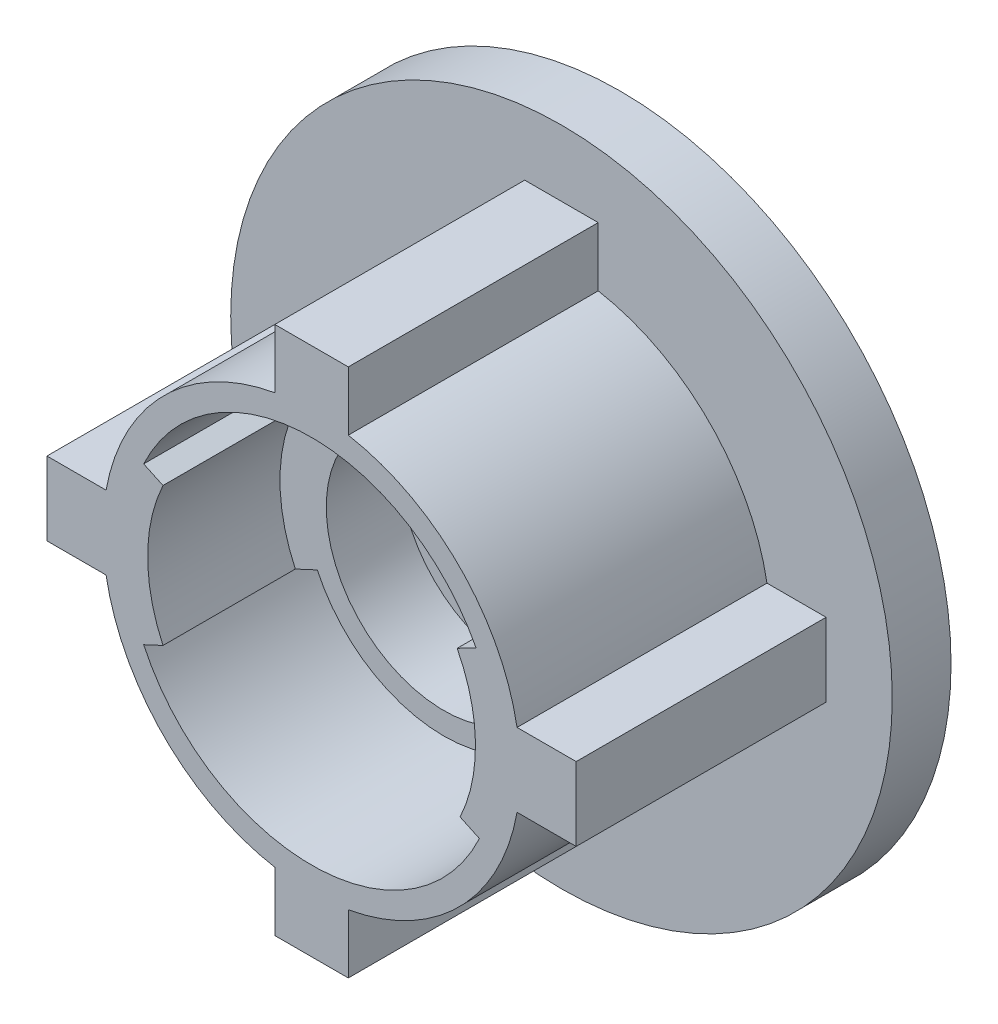
SolidWorks part; units mm, degrees
ref_plane "Plano frontal" through (0, 0, 0) normal (0, 0, 1) x (1, 0, 0)
ref_plane "Plano superior" through (0, 0, 0) normal (0, 1, 0) x (1, 0, 0)
ref_plane "Plano direito" through (0, 0, 0) normal (1, 0, 0) x (0, 0, -1)
sketch "Esboço1" plane through (0, 0, 0) normal (0, 0, 1) x (1, 0, 0)
  line L0 (18, 2.5) -> (13.9782, 2.5)
  line L1 (18, -2.5) -> (18, 2.5)
  line L2 (13.9782, -2.5) -> (18, -2.5)
  line L3 (2.5, -18) -> (2.5, -13.9782)
  line L4 (-2.5, -18) -> (2.5, -18)
  line L5 (-2.5, -13.9782) -> (-2.5, -18)
  line L6 (-18, -2.5) -> (-13.9782, -2.5)
  line L7 (-18, 2.5) -> (-18, -2.5)
  line L8 (-13.9782, 2.5) -> (-18, 2.5)
  line L9 (-2.5, 18) -> (-2.5, 13.9782)
  line L10 (2.5, 18) -> (-2.5, 18)
  line L11 (2.5, 13.9782) -> (2.5, 18)
  circle A0 centre (0, 0) radius 11.15
  circle A1 centre (0, 0) radius 6.1
  circle A3 centre (0, 0) radius 4.3
  arc A4 (-13.9782, -2.5) -> (-2.5, -13.9782) centre (0, 0) ccw
  arc A5 (13.9782, 2.5) -> (2.5, 13.9782) centre (0, 0) ccw
  arc A6 (2.5, -13.9782) -> (13.9782, -2.5) centre (0, 0) ccw
  arc A7 (-13.9782, -2.5) -> (-2.5, -13.9782) centre (0, 0) ccw
  arc A8 (-2.5, 13.9782) -> (-13.9782, 2.5) centre (0, 0) ccw
  arc A9 (-2.5, 13.9782) -> (-13.9782, 2.5) centre (0, 0) ccw
  arc A10 (13.9782, 2.5) -> (2.5, 13.9782) centre (0, 0) ccw
  arc A11 (2.5, -13.9782) -> (13.9782, -2.5) centre (0, 0) ccw
  dimension "D1" = 28.4
  dimension "D2" = 8.6
  dimension "D3" = 12.2
  dimension "D5" = 22.3
  dimension "D6" = 14.2
  dimension "D7" = 14.2
  dimension "D8" = 14.2
  dimension "D9" = 14.2
  dimension "D10" = 2.5
  dimension "D11" = 2.5
  dimension "D12" = 13.9782
  dimension "D13" = 13.9782
  dimension "D14" = 18
  dimension "D15" = 18
  dimension "D16" = 2.5
  dimension "D17" = 2.5
  dimension "D18" = 13.9782
  dimension "D19" = 13.9782
  dimension "D20" = 18
  dimension "D21" = 18
  dimension "D22" = 2.5
  dimension "D23" = 2.5
  dimension "D24" = 13.9782
  dimension "D25" = 13.9782
  dimension "D26" = 18
  dimension "D27" = 18
  dimension "D28" = 2.5
  dimension "D29" = 2.5
  dimension "D30" = 13.9782
  dimension "D31" = 13.9782
  dimension "D32" = 18
  dimension "D33" = 18
extrude "Ressalto-extrusão1" add sketch "Esboço1" along normal blind 15 contours L9 A8 L8 L7 L6 A4 L5 L4 L3 A6 L2 L1 L0 A5 L11 L10 A0
sketch "Esboço2" plane through (0, 0, 0) normal (0, 0, -1) x (-1, 0, 0)
  line L4 (2.5, 18) -> (2.5, 13.9782) construction
  line L5 (-2.5, 18) -> (2.5, 18) construction
  circle A0 centre (0, 0) radius 22.5
  arc A9 (2.5, 13.9782) -> (-13.9782, -2.5) centre (0, 0) ccw
  arc A10 (-13.9782, -2.5) -> (2.5, -13.9782) centre (0, 0) ccw
  arc A11 (-2.5, -13.9782) -> (13.9782, -2.5) centre (0, 0) ccw
  arc A12 (13.9782, -2.5) -> (2.5, 13.9782) centre (0, 0) ccw
  line M18 (2.5, 13.9782) -> (2.5, 18)
  line M19 (2.5, 18) -> (-2.5, 18)
  line M20 (-2.5, 18) -> (-2.5, 13.9782)
  arc M21 (-2.5, 13.9782) -> (-13.9782, 2.5) centre (0, 0) ccw
  line M22 (-13.9782, 2.5) -> (-18, 2.5)
  line M23 (-18, 2.5) -> (-18, -2.5)
  line M24 (-18, -2.5) -> (-13.9782, -2.5)
  arc M25 (-13.9782, -2.5) -> (-2.5, -13.9782) centre (0, 0) ccw
  line M26 (-2.5, -13.9782) -> (-2.5, -18)
  line M27 (-2.5, -18) -> (2.5, -18)
  line M28 (2.5, -18) -> (2.5, -13.9782)
  arc M29 (2.5, -13.9782) -> (13.9782, -2.5) centre (0, 0) ccw
  line M30 (13.9782, -2.5) -> (18, -2.5)
  line M31 (18, -2.5) -> (18, 2.5)
  line M32 (18, 2.5) -> (13.9782, 2.5)
  arc M33 (13.9782, 2.5) -> (2.5, 13.9782) centre (0, 0) ccw
  dimension "D1" = 45
  dimension "D2" = 14.2
  dimension "D3" = 14.2
  dimension "D4" = 14.2
  dimension "D5" = 14.2
  dimension "D6" = 11.4782
  dimension "D7" = 2.5
  dimension "D8" = 5
  dimension "D9" = 16.4782
  dimension "D10" = 4.0218
  dimension "D11" = 18
  dimension "D12" = 31.9782
  dimension "D14" = 20.5
  dimension "D15" = 20.5
  dimension "D16" = 31.9782
extrude "Ressalto-extrusão2" add sketch "Esboço2" along normal blind 4 separate body contours A0 M18 M33 M32 M31 M30 M29 M28 M27 M26 M25 M24 M23 M22 M21 M20 M19 | A10 M26 M27 M28 | A9 M22 M23 M24 | A9 M18 M19 M20 | A12 M30 M31 M32
sketch "Esboço5" plane through (0, 0, 15) normal (0, 0, 1) x (1, 0, 0)
  circle A0 centre (0, 0) radius 11.15 construction
  circle A1 centre (0, 0) radius 11.15
  circle A2 centre (0, 0) radius 8
  dimension "D1" = 16
extrude "Ressalto-extrusão6" add sketch "Esboço5" against normal blind 8
sketch "Esboço7" plane through (0, 0, 0) normal (0, 0, -1) x (-1, 0, 0)
  circle A0 centre (0, 0) radius 11.15 construction
  circle A1 centre (0, 0) radius 14.2 construction
  circle A2 centre (0, 0) radius 11.15
  circle A3 centre (0, 0) radius 14.2
extrude "Ressalto-extrusão7" add sketch "Esboço7" along normal up to surface (4 mm away) up to face at (-14.2, 0, -4)
sketch "Esboço8" plane through (0, 0, 7) normal (0, 0, -1) x (-1, 0, 0)
  circle A0 centre (0, 0) radius 8 construction
  circle A1 centre (0, 0) radius 11.15 construction
  circle A2 centre (0, 0) radius 8
  circle A3 centre (0, 0) radius 11.15
extrude "Ressalto-extrusão8" add sketch "Esboço8" along normal blind 4
sketch "Esboço11" plane through (0, 0, 15) normal (0, 0, 1) x (1, 0, 0)
  line L0 (-11.1912, -5.7895) -> (-8.4378, -4.3651)
  line L1 (-11.4195, 5.325) -> (-8.6099, 4.0149)
  line L2 (8.6099, -4.0149) -> (11.4195, -5.325)
  line L3 (8.4378, 4.3651) -> (11.1912, 5.7895)
  arc A2 (-8.4378, -4.3651) -> (8.6099, -4.0149) centre (0, 0) ccw
  arc A3 (-11.1912, -5.7895) -> (11.4195, -5.325) centre (0, 0) ccw
  arc A4 (8.4378, 4.3651) -> (-8.6099, 4.0149) centre (0, 0) ccw
  arc A5 (11.1912, 5.7895) -> (-11.4195, 5.325) centre (0, 0) ccw
  dimension "D1" = 19
  dimension "D2" = 25.2
extrude "Corte-extrusão1" cut sketch "Esboço11" against normal blind 7
sketch "Esboço12" plane through (0, 0, 8) normal (0, 0, 1) x (1, 0, 0)
  line L0 (11.4195, -5.325) -> (8.6099, -4.0149) construction
  line L1 (-8.4378, -4.3651) -> (-11.1912, -5.7895) construction
  line L2 (-11.4195, 5.325) -> (-8.6099, 4.0149) construction
  line L3 (8.4378, 4.3651) -> (11.1912, 5.7895) construction
  line L4 (11.4195, -5.325) -> (8.6099, -4.0149)
  line L5 (-8.4378, -4.3651) -> (-11.1912, -5.7895)
  line L6 (-11.4195, 5.325) -> (-8.6099, 4.0149)
  line L7 (8.4378, 4.3651) -> (11.1912, 5.7895)
  arc A0 (-11.1912, -5.7895) -> (11.4195, -5.325) centre (0, 0) ccw construction
  arc A1 (-8.4378, -4.3651) -> (8.6099, -4.0149) centre (0, 0) ccw construction
  arc A2 (11.1912, 5.7895) -> (-11.4195, 5.325) centre (0, 0) ccw construction
  arc A3 (8.4378, 4.3651) -> (-8.6099, 4.0149) centre (0, 0) ccw construction
  arc A4 (-11.1912, -5.7895) -> (11.4195, -5.325) centre (0, 0) ccw
  arc A5 (-8.4378, -4.3651) -> (8.6099, -4.0149) centre (0, 0) ccw
  arc A6 (11.1912, 5.7895) -> (-11.4195, 5.325) centre (0, 0) ccw
  arc A7 (8.4378, 4.3651) -> (-8.6099, 4.0149) centre (0, 0) ccw
extrude "Corte-extrusão2" cut sketch "Esboço12" against normal up to surface (8 mm away) up to face at (-22.5, 0, 0)
sketch "Esboço13" plane through (0, 0, 15) normal (0, 0, 1) x (1, 0, 0)
  line L12 (-2.5, 18) -> (-2.5, 13.9782)
  line L13 (-13.9782, 2.5) -> (-18, 2.5)
  line L14 (-18, 2.5) -> (-18, -2.5)
  line L15 (-18, -2.5) -> (-13.9782, -2.5)
  line L16 (-2.5, -13.9782) -> (-2.5, -18)
  line L17 (-2.5, -18) -> (2.5, -18)
  line L18 (2.5, -18) -> (2.5, -13.9782)
  line L19 (13.9782, -2.5) -> (18, -2.5)
  line L20 (18, -2.5) -> (18, 2.5)
  line L21 (18, 2.5) -> (13.9782, 2.5)
  line L22 (2.5, 13.9782) -> (2.5, 18)
  line L23 (2.5, 18) -> (-2.5, 18)
  line L24 (-2.5, 18) -> (-2.5, 13.9782)
  line L25 (-13.9782, 2.5) -> (-18, 2.5)
  line L26 (-18, 2.5) -> (-18, -2.5)
  line L27 (-18, -2.5) -> (-13.9782, -2.5)
  line L28 (-2.5, -13.9782) -> (-2.5, -18)
  line L29 (-2.5, -18) -> (2.5, -18)
  line L30 (2.5, -18) -> (2.5, -13.9782)
  line L31 (13.9782, -2.5) -> (18, -2.5)
  line L32 (18, -2.5) -> (18, 2.5)
  line L33 (18, 2.5) -> (13.9782, 2.5)
  line L34 (2.5, 13.9782) -> (2.5, 18)
  line L35 (2.5, 18) -> (-2.5, 18)
  arc A4 (-2.5, 13.9782) -> (-13.9782, 2.5) centre (0, 0) ccw
  arc A5 (-13.9782, -2.5) -> (-2.5, -13.9782) centre (0, 0) ccw
  arc A6 (2.5, -13.9782) -> (13.9782, -2.5) centre (0, 0) ccw
  arc A7 (13.9782, 2.5) -> (2.5, 13.9782) centre (0, 0) ccw
  arc A8 (-2.5, 13.9782) -> (-13.9782, 2.5) centre (0, 0) ccw
  arc A9 (-13.9782, -2.5) -> (-2.5, -13.9782) centre (0, 0) ccw
  arc A10 (2.5, -13.9782) -> (13.9782, -2.5) centre (0, 0) ccw
  arc A11 (13.9782, 2.5) -> (2.5, 13.9782) centre (0, 0) ccw
  dimension "D1" = 0
extrude "Corte-extrusão3" cut sketch "Esboço13" against normal blind 4
sketch "Esboço14" plane through (0, 0, 11) normal (0, 0, 1) x (1, 0, 0)
  line L0 (11.1912, 5.7895) -> (8.4378, 4.3651) construction
  line L1 (-8.6099, 4.0149) -> (-11.4195, 5.325) construction
  line L2 (11.1912, 5.7895) -> (8.4378, 4.3651)
  line L3 (-8.6099, 4.0149) -> (-11.4195, 5.325)
  line L4 (0, 0) -> (5.7325, 0) construction
  line L5 (-8.6099, -4.0149) -> (-11.4195, -5.325)
  line L7 (-11.1912, -5.7895) -> (-8.4378, -4.3651) construction
  line L8 (-11.1912, -5.7895) -> (-8.4378, -4.3651)
  arc A0 (8.4378, 4.3651) -> (-8.6099, 4.0149) centre (0, 0) ccw construction
  arc A1 (11.1912, 5.7895) -> (-11.4195, 5.325) centre (0, 0) ccw construction
  arc A2 (8.4378, 4.3651) -> (-8.6099, 4.0149) centre (0, 0) ccw
  arc A3 (11.1912, 5.7895) -> (-11.4195, 5.325) centre (0, 0) ccw
  arc A4 (-11.1912, -5.7895) -> (-11.4195, -5.325) centre (0, 0) cw
  arc A5 (-8.4378, -4.3651) -> (-8.6099, -4.0149) centre (0, 0) cw
extrude "Corte-extrusão4" cut sketch "Esboço14" against normal up to surface (11 mm away)
sketch "Esboço17" plane through (0, 0, 11) normal (0, 0, 1) x (1, 0, 0)
  circle A0 centre (0, 0) radius 11.15
  dimension "D1" = 22.3
extrude "Corte-extrusão5" cut sketch "Esboço17" against normal blind 3
sketch "Esboço18" plane through (0, 0, 11) normal (0, 0, 1) x (1, 0, 0)
  line L0 (11.4195, -5.325) -> (10.1053, -4.7122) construction
  line L1 (-11.4195, 5.325) -> (-10.1053, 4.7122) construction
  line L2 (11.4195, -5.325) -> (10.1053, -4.7122)
  line L3 (-11.4195, 5.325) -> (-10.1053, 4.7122)
  line L4 (-11.4195, 5.325) -> (-10.1053, 4.7122)
  line L5 (9.9033, 5.1232) -> (11.1912, 5.7895)
  line L6 (11.4195, -5.325) -> (10.1053, -4.7122)
  line L7 (-10.1053, -4.7122) -> (-11.4195, -5.325)
  line L8 (-11.4195, 5.325) -> (-10.1053, 4.7122)
  line L9 (9.9033, 5.1232) -> (11.1912, 5.7895)
  line L10 (11.4195, -5.325) -> (10.1053, -4.7122)
  line L11 (-10.1053, -4.7122) -> (-11.4195, -5.325)
  line L12 (2.5, 18) -> (-2.5, 18)
  line L13 (-2.5, 18) -> (-2.5, 13.9782)
  line L14 (-13.9782, 2.5) -> (-18, 2.5)
  line L15 (-18, 2.5) -> (-18, -2.5)
  line L16 (-18, -2.5) -> (-13.9782, -2.5)
  line L17 (-2.5, -13.9782) -> (-2.5, -18)
  line L18 (-2.5, -18) -> (2.5, -18)
  line L19 (2.5, -18) -> (2.5, -13.9782)
  line L20 (13.9782, -2.5) -> (18, -2.5)
  line L21 (18, -2.5) -> (18, 2.5)
  line L22 (18, 2.5) -> (13.9782, 2.5)
  line L23 (2.5, 13.9782) -> (2.5, 18)
  line L24 (2.5, 18) -> (-2.5, 18)
  line L25 (-2.5, 18) -> (-2.5, 13.9782)
  line L26 (-13.9782, 2.5) -> (-18, 2.5)
  line L27 (-18, 2.5) -> (-18, -2.5)
  line L28 (-18, -2.5) -> (-13.9782, -2.5)
  line L29 (-2.5, -13.9782) -> (-2.5, -18)
  line L30 (-2.5, -18) -> (2.5, -18)
  line L31 (2.5, -18) -> (2.5, -13.9782)
  line L32 (13.9782, -2.5) -> (18, -2.5)
  line L33 (18, -2.5) -> (18, 2.5)
  line L34 (18, 2.5) -> (13.9782, 2.5)
  line L35 (2.5, 13.9782) -> (2.5, 18)
  arc A0 (11.1912, 5.7895) -> (-11.4195, 5.325) centre (0, 0) ccw construction
  arc A1 (-10.1053, 4.7122) -> (-10.1053, -4.7122) centre (0, 0) ccw construction
  arc A2 (11.1912, 5.7895) -> (-11.4195, 5.325) centre (0, 0) ccw
  arc A3 (-10.1053, 4.7122) -> (-10.1053, -4.7122) centre (0, 0) ccw
  arc A4 (-2.5, 13.9782) -> (-13.9782, 2.5) centre (0, 0) ccw
  arc A5 (-13.9782, -2.5) -> (-2.5, -13.9782) centre (0, 0) ccw
  arc A6 (2.5, -13.9782) -> (13.9782, -2.5) centre (0, 0) ccw
  arc A7 (13.9782, 2.5) -> (2.5, 13.9782) centre (0, 0) ccw
  arc A8 (-2.5, 13.9782) -> (-13.9782, 2.5) centre (0, 0) ccw
  arc A9 (-13.9782, -2.5) -> (-2.5, -13.9782) centre (0, 0) ccw
  arc A10 (2.5, -13.9782) -> (13.9782, -2.5) centre (0, 0) ccw
  arc A11 (13.9782, 2.5) -> (2.5, 13.9782) centre (0, 0) ccw
  arc A12 (-10.1053, 4.7122) -> (-10.1053, -4.7122) centre (0, 0) ccw
  arc A13 (11.1912, 5.7895) -> (-11.4195, 5.325) centre (0, 0) ccw
  arc A14 (10.1053, -4.7122) -> (9.9033, 5.1232) centre (0, 0) ccw
  arc A15 (-11.4195, -5.325) -> (11.4195, -5.325) centre (0, 0) ccw
  arc A16 (-10.1053, 4.7122) -> (-10.1053, -4.7122) centre (0, 0) ccw
  arc A17 (11.1912, 5.7895) -> (-11.4195, 5.325) centre (0, 0) ccw
  arc A18 (10.1053, -4.7122) -> (9.9033, 5.1232) centre (0, 0) ccw
  arc A19 (-11.4195, -5.325) -> (11.4195, -5.325) centre (0, 0) ccw
  arc M25 (-10.1053, -4.7122) -> (-10.1053, 4.7122) centre (0, 0) cw
  line M26 (-10.1053, 4.7122) -> (-11.4195, 5.325)
  arc M27 (-11.4195, 5.325) -> (11.1912, 5.7895) centre (0, 0) cw
  line M28 (11.1912, 5.7895) -> (9.9033, 5.1232)
  arc M29 (9.9033, 5.1232) -> (10.1053, -4.7122) centre (0, 0) cw
  line M30 (10.1053, -4.7122) -> (11.4195, -5.325)
  arc M31 (11.4195, -5.325) -> (-11.4195, -5.325) centre (0, 0) cw
  line M32 (-11.4195, -5.325) -> (-10.1053, -4.7122)
  line M33 (2.5, 18) -> (-2.5, 18)
  line M34 (-2.5, 18) -> (-2.5, 13.9782)
  arc M35 (-2.5, 13.9782) -> (-13.9782, 2.5) centre (0, 0) ccw
  line M36 (-13.9782, 2.5) -> (-18, 2.5)
  line M37 (-18, 2.5) -> (-18, -2.5)
  line M38 (-18, -2.5) -> (-13.9782, -2.5)
  arc M39 (-13.9782, -2.5) -> (-2.5, -13.9782) centre (0, 0) ccw
  line M40 (-2.5, -13.9782) -> (-2.5, -18)
  line M41 (-2.5, -18) -> (2.5, -18)
  line M42 (2.5, -18) -> (2.5, -13.9782)
  arc M43 (2.5, -13.9782) -> (13.9782, -2.5) centre (0, 0) ccw
  line M44 (13.9782, -2.5) -> (18, -2.5)
  line M45 (18, -2.5) -> (18, 2.5)
  line M46 (18, 2.5) -> (13.9782, 2.5)
  arc M47 (13.9782, 2.5) -> (2.5, 13.9782) centre (0, 0) ccw
  line M48 (2.5, 13.9782) -> (2.5, 18)
  dimension "D1" = 0
  dimension "D2" = 0
extrude "Ressalto-extrusão11" add sketch "Esboço18" along normal blind 6 contours M48 M33 M34 M35 M36 M37 M38 M39 M40 M41 M42 M43 M44 M45 M46 M47 M32 M25 M26 M27 M28 M29 M30 M31
